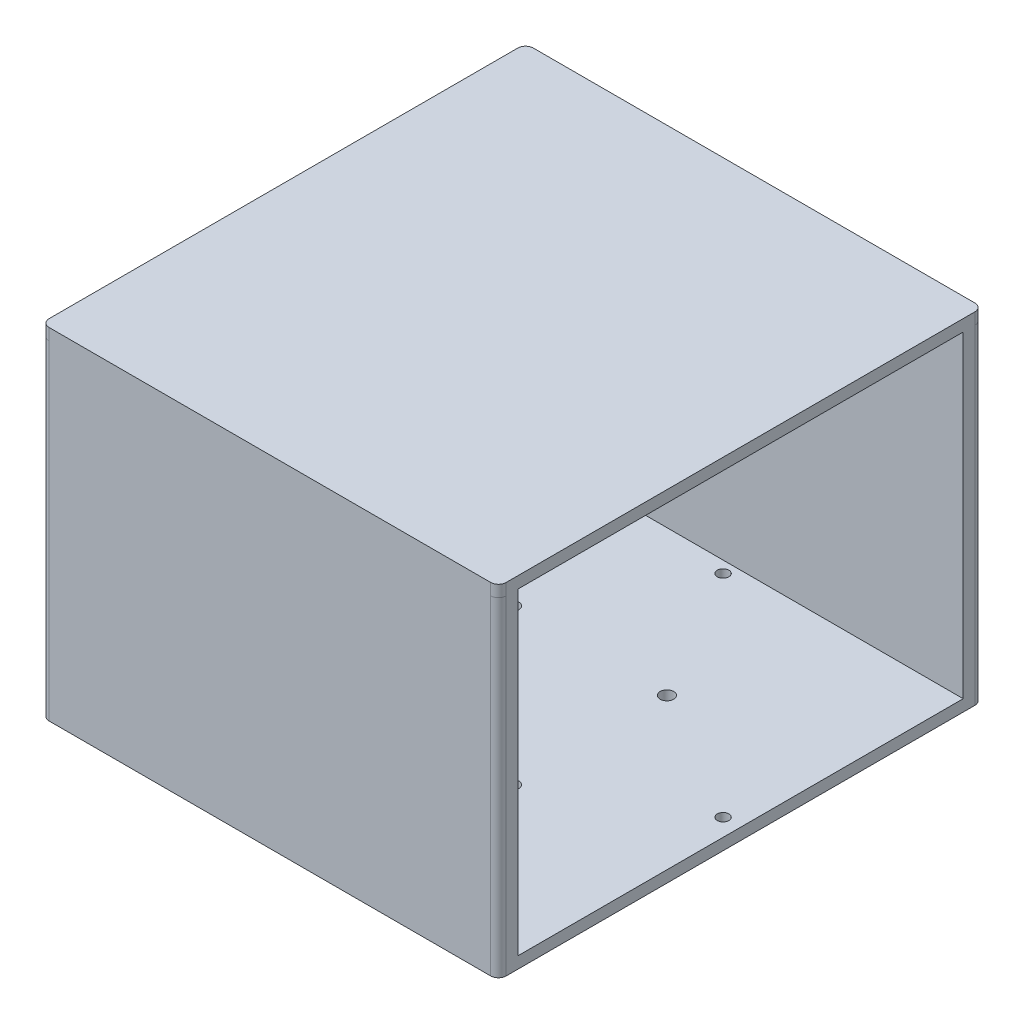
SolidWorks part; units mm, degrees
ref_plane "前视基准面" through (0, 0, 0) normal (0, 0, 1) x (1, 0, 0)
ref_plane "上视基准面" through (0, 0, 0) normal (0, 1, 0) x (1, 0, 0)
ref_plane "右视基准面" through (0, 0, 0) normal (1, 0, 0) x (0, 0, -1)
sketch "草图1" plane through (0, 0, 0) normal (0, 1, 0) x (1, 0, 0)
  line L0 (0, 0) -> (-17.8258, 0) construction
  line L1 (0, 0) -> (0, 11.9102) construction
  line L3 (59, 62.5) -> (-59, 62.5)
  line L4 (59, 62.5) -> (59, -62.5)
  line L5 (59, -62.5) -> (-59, -62.5)
  line L6 (-59, 62.5) -> (-59, -62.5)
  line L7 (59, 62.5) -> (-59, -62.5) construction
  line L8 (59, -62.5) -> (-59, 62.5) construction
  circle A0 centre (-54.5, 0) radius 1.5
  circle A1 centre (0, 54.5) radius 1.5
  circle A2 centre (54.5, 0) radius 1.5
  circle A3 centre (0, -54.5) radius 1.5
  point P2 (0, 0)
  dimension "D3" = 54.5
  dimension "D1" = 125
  dimension "D2" = 118
  dimension "D4" = 54.5
  dimension "D5" = 54.5
  dimension "D6" = 54.5
extrude "凸台-拉伸1" add sketch "草图1" along normal blind 3
sketch "草图5" plane through (0, 0, 0) normal (0, -1, 0) x (-1, 0, 0)
  line L0 (0, 0) -> (13.682, 0) construction
  line L1 (0, 0) -> (0, -6.9102) construction
  circle A0 centre (20, 20) radius 1.75
  circle A1 centre (-20, 20) radius 1.75
  circle A2 centre (-20, -20) radius 1.75
  circle A3 centre (20, -20) radius 1.75
  point P13 (0, 0)
  point P16 (-19.169, 0)
extrude "切除-拉伸1" cut sketch "草图5" against normal blind 10
sketch "草图6" plane through (0, 3, 0) normal (0, 1, 0) x (1, 0, 0)
  line L0 (-59, 62.5) -> (-59, -62.5) construction
  line L1 (59, -62.5) -> (-59, -62.5)
  line L2 (59, -62.5) -> (59, -57.5)
  line L3 (59, -57.5) -> (-59, -57.5)
  line L4 (-59, -62.5) -> (-59, -57.5)
  line L5 (59, -62.5) -> (-59, -57.5) construction
  line L6 (59, -57.5) -> (-59, -62.5) construction
  line L8 (59, 62.5) -> (-59, 62.5)
  line L9 (59, 62.5) -> (59, 57.5)
  line L10 (59, 57.5) -> (-59, 57.5)
  line L11 (-59, 62.5) -> (-59, 57.5)
  line L12 (59, 62.5) -> (-59, 57.5) construction
  line L13 (59, 57.5) -> (-59, 62.5) construction
  point P4 (0, -60)
  point P12 (0, 60)
  dimension "D1" = 5
  dimension "D2" = 5
extrude "凸台-拉伸4" add sketch "草图6" along normal blind 82
fillet "圆角1" radius 2 4 edges at (59, 42.5, 62.5) (-59, 42.5, -62.5) (59, 42.5, -62.5) (-59, 42.5, 62.5)
sketch "草图7" plane through (0, 85, 0) normal (0, 1, 0) x (1, 0, 0)
  line L1 (59, 62.5) -> (-59, 62.5)
  line L2 (59, 62.5) -> (59, -62.5)
  line L3 (59, -62.5) -> (-59, -62.5)
  line L4 (-59, 62.5) -> (-59, -62.5)
  line L5 (59, 62.5) -> (-59, -62.5) construction
  line L6 (59, -62.5) -> (-59, 62.5) construction
  point P0 (0, 0)
extrude "凸台-拉伸5" add sketch "草图7" along normal blind 3
fillet "圆角2" radius 2 4 edges at (-59, 86.5, -62.5) (59, 86.5, -62.5) (-59, 86.5, 62.5) (59, 86.5, 62.5)
